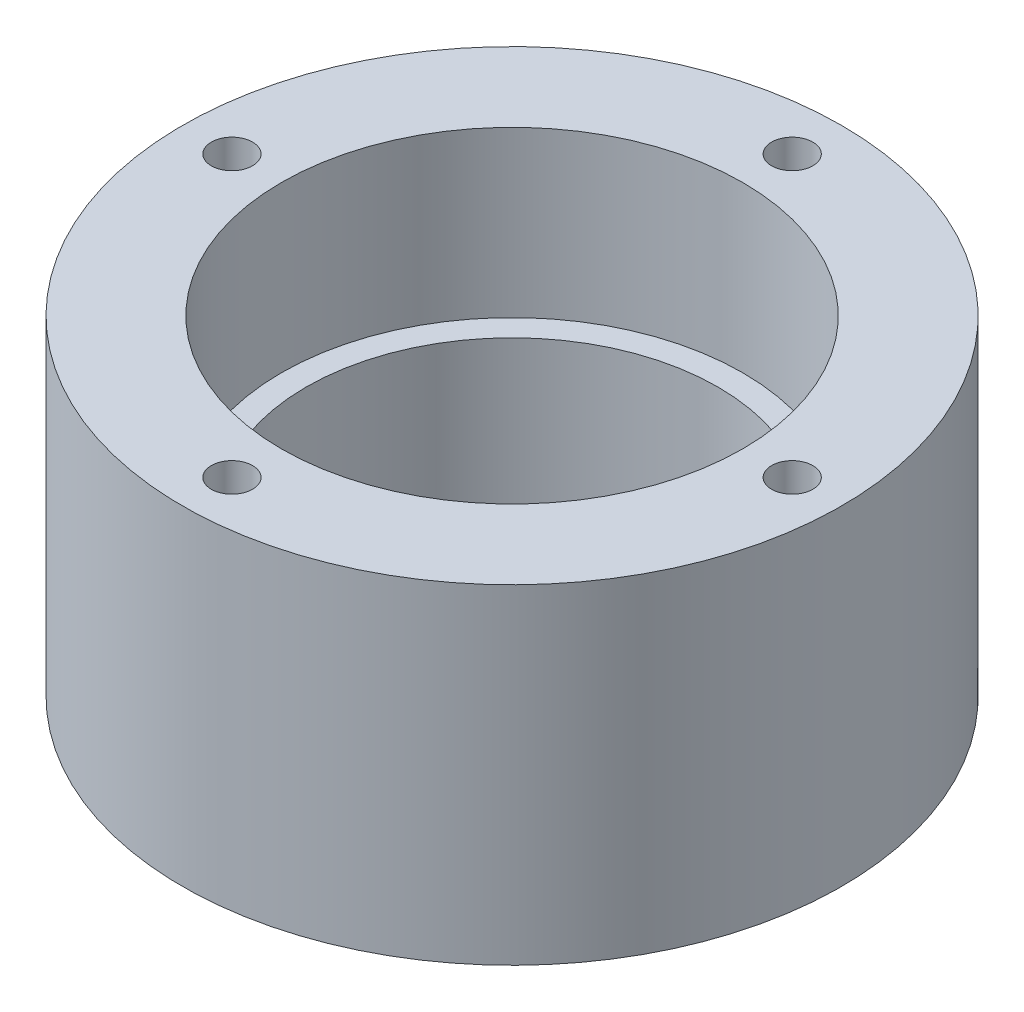
SolidWorks part; units mm, degrees
material "6061"
ref_plane "Front" through (0, 0, 0) normal (0, 0, 1) x (1, 0, 0)
ref_plane "Top" through (0, 0, 0) normal (0, 1, 0) x (1, 0, 0)
ref_plane "Right" through (0, 0, 0) normal (1, 0, 0) x (0, 0, -1)
sketch "Sketch1" plane through (0, 0, 0) normal (0, 0, 1) x (1, 0, 0)
  line L0 (0, -15.5291) -> (0, 94.8161) construction
  line L2 (12.5, 0) -> (20, 0)
  line L3 (12.5, 0) -> (12.5, 20)
  line L4 (12.5, 20) -> (20, 20)
  line L5 (20, 0) -> (20, 20)
  dimension "D1" = 40
  dimension "D2" = 20
  dimension "D3" = 25
revolve "Revolve1" add sketch "Sketch1" angle 360 about L0
sketch "Sketch2" plane through (0, 0, 0) normal (0, 0, 1) x (1, 0, 0)
  line L0 (0, -1.5479) -> (0, 22.07) construction
  line L1 (20, 20) -> (-20, 20) construction
  line L2 (12.5, 20) -> (14, 20)
  line L3 (12.5, 20) -> (12.5, 10)
  line L4 (12.5, 10) -> (14, 10)
  line L5 (14, 20) -> (14, 10)
  line L6 (12.5, 0) -> (12.5, 20) construction
  dimension "D1" = 28
  dimension "D2" = 10
revolve "Cut-Revolve1" cut sketch "Sketch2" angle 360 about L0
hole_wizard "M3x0.5 Tapped Hole1" positions "Sketch4" profile "Sketch3" tap size "M3x0.5" standard "JIS"
sketch "Sketch4" plane through (0, 20, 0) normal (0, 1, 0) x (-1, 0, 0)
  circle A0 centre (0, 0) radius 17 construction
  point P0 (17, 0)
  point P1 (-17, 0)
  point P3 (0, -17)
  point P5 (0, 17)
  dimension "D1" = 34
sketch "Sketch3" plane through (-17, 20, 0) normal (1, 0, 0) x (0, 0, 1)
  line L0 (0, 0) -> (0, 9.2511)
  line L1 (0, 9.2511) -> (1.25, 8.5)
  line L2 (1.25, 8.5) -> (1.25, 0)
  line L5 (1.25, 0) -> (0, 0)
  line L10 (0, 9.2511) -> (-1.25, 8.5) construction
  line L11 (0, -6.35) -> (0, 107.95) construction
  dimension "Tap Drill Dia." = 2.5
  dimension "Tap Drill Depth" = 8.5
  dimension "Drill Angle" = 118
cosmetic thread "Hole Thread1" parameters "D1"=6, "D2"=3
cosmetic thread "Hole Thread2" parameters "D1"=6, "D2"=3
cosmetic thread "Hole Thread3" parameters "D1"=6, "D2"=3
cosmetic thread "Hole Thread4" parameters "D1"=6, "D2"=3
